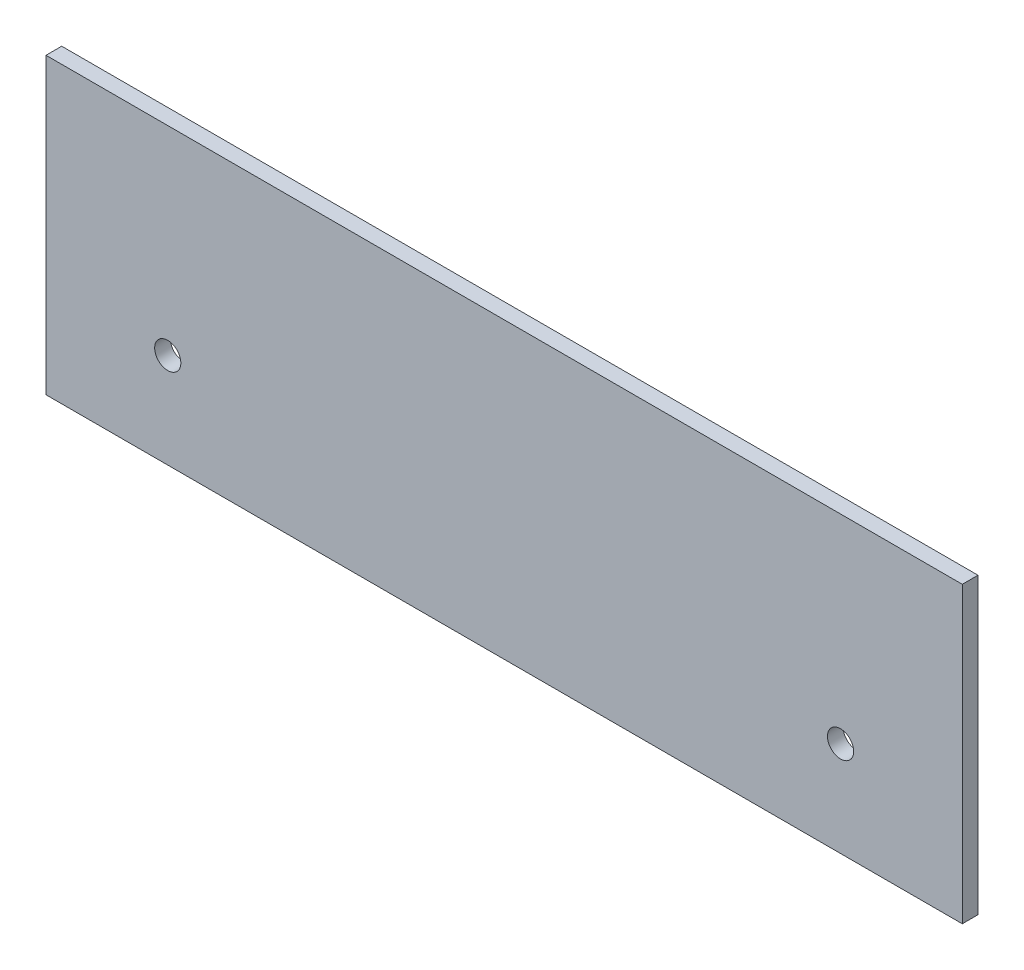
SolidWorks part; units mm, degrees
material "Custom Plastic"
ref_plane "Plan de face" through (0, 0, 0) normal (0, 0, 1) x (1, 0, 0)
ref_plane "Plan de dessus" through (0, 0, 0) normal (0, 1, 0) x (1, 0, 0)
ref_plane "Plan de droite" through (0, 0, 0) normal (1, 0, 0) x (0, 0, -1)
sketch "Esquisse2" plane through (0, 0, 0) normal (0, 1, 0) x (1, 0, 0)
  line L0 (-76.2817, -46.3798) -> (-76.2817, -1.166) construction
  line L1 (-76.2817, -1.166) -> (98.7183, -1.166)
  line L2 (-76.2817, -1.166) -> (-76.2817, -4.166)
  line L3 (-76.2817, -4.166) -> (98.7183, -4.166)
  line L4 (98.7183, -1.166) -> (98.7183, -4.166)
  line L5 (-76.2817, -1.166) -> (98.7183, -4.166) construction
  line L6 (-76.2817, -4.166) -> (98.7183, -1.166) construction
  line L14 (98.7183, -65.8798) -> (98.7183, -1.166) construction
  point P4 (11.2183, -2.666)
  dimension "D1" = 3
extrude "Boss.-Extru.1" add sketch "Esquisse2" along normal up to surface (36.27 mm away)
sketch "Esquisse3" plane through (0, 0, 4.166) normal (0, 0, 1) x (1, 0, 0)
  line L1 (88.9683, 84.4923) -> (88.9683, -49694.1144) construction
  line L2 (-66.5317, 18.135) -> (88.9683, 18.135) construction
  line L3 (88.9683, 18.135) -> (98.7183, 18.135) construction
  line L4 (98.7183, 36.27) -> (98.7183, 0) construction
  line L5 (-66.5317, 18.135) -> (-76.2817, 18.135) construction
  line L6 (-76.2817, 36.27) -> (-76.2817, 0) construction
  line L7 (-76.2817, 36.27) -> (98.7183, 36.27) construction
  line L8 (11.2183, 36.27) -> (11.2183, 0) construction
  line L10 (98.7183, 36.27) -> (-76.2817, 36.27) construction
  line L11 (-76.2817, 0) -> (98.7183, 0) construction
  line L12 (-66.5317, 36.27) -> (-66.5317, 18.135) construction
  line L13 (-66.5317, 18.135) -> (-66.5317, 0) construction
  circle A6 centre (-53.0317, 18.135) radius 2.5
  circle A7 centre (75.4683, 18.135) radius 2.5
  point P12 (11.2183, 18.135)
  dimension "D2" = 5
  dimension "D1" = 5
  dimension "D3" = 13.5
  dimension "D4" = 13.5
extrude "Enlèv. mat.-Extru.1" cut sketch "Esquisse3" against normal through all
sketch "Sketch1" plane through (0, 0, 4.166) normal (0, 0, 1) x (1, 0, 0)
  line L1 (-76.2817, 36.27) -> (98.7183, 36.27)
  line L2 (-76.2817, 36.27) -> (-76.2817, 56.1575)
  line L3 (-76.2817, 56.1575) -> (98.7183, 56.1575)
  line L4 (98.7183, 36.27) -> (98.7183, 56.1575)
  dimension "D1" = 19.8875
extrude "Boss-Extrude1" add sketch "Sketch1" against normal up to surface (3 mm away) up to face at (-50.5317, 18.135, 1.166)
